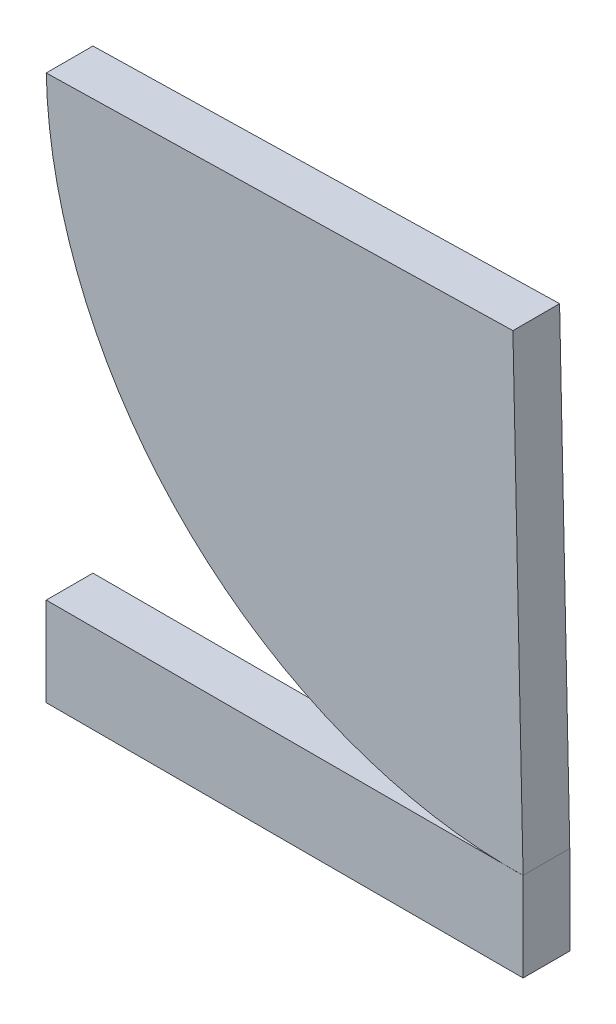
SolidWorks part; units mm, degrees
ref_plane "正面" through (0, 0, 0) normal (0, 0, 1) x (1, 0, 0)
ref_plane "平面" through (0, 0, 0) normal (0, 1, 0) x (1, 0, 0)
ref_plane "右側面" through (0, 0, 0) normal (1, 0, 0) x (0, 0, -1)
sketch "ｽｹｯﾁ1" plane through (0, 0, 0) normal (0, 0, 1) x (1, 0, 0)
  line L0 (-9.9976, -0.2181) -> (0, 0)
  line L1 (0, 0) -> (0.2181, -9.9976)
  line L3 (0.2181, -9.9976) -> (-9.9976, -9.9976)
  line L4 (0.2181, -9.9976) -> (0.2181, -11.9014)
  line L5 (0.2181, -11.9014) -> (-9.9976, -11.9014)
  line L6 (-9.9976, -9.9976) -> (-9.9976, -11.9014)
  arc A0 (0.2181, -9.9976) -> (-9.9976, -0.2181) centre (0, 0) cw
extrude "ﾎﾞｽ - 押し出し1" add sketch "ｽｹｯﾁ1" along normal blind 1 contours A0 L3 L1 L0 | L4 A0 L3 L6 L5
